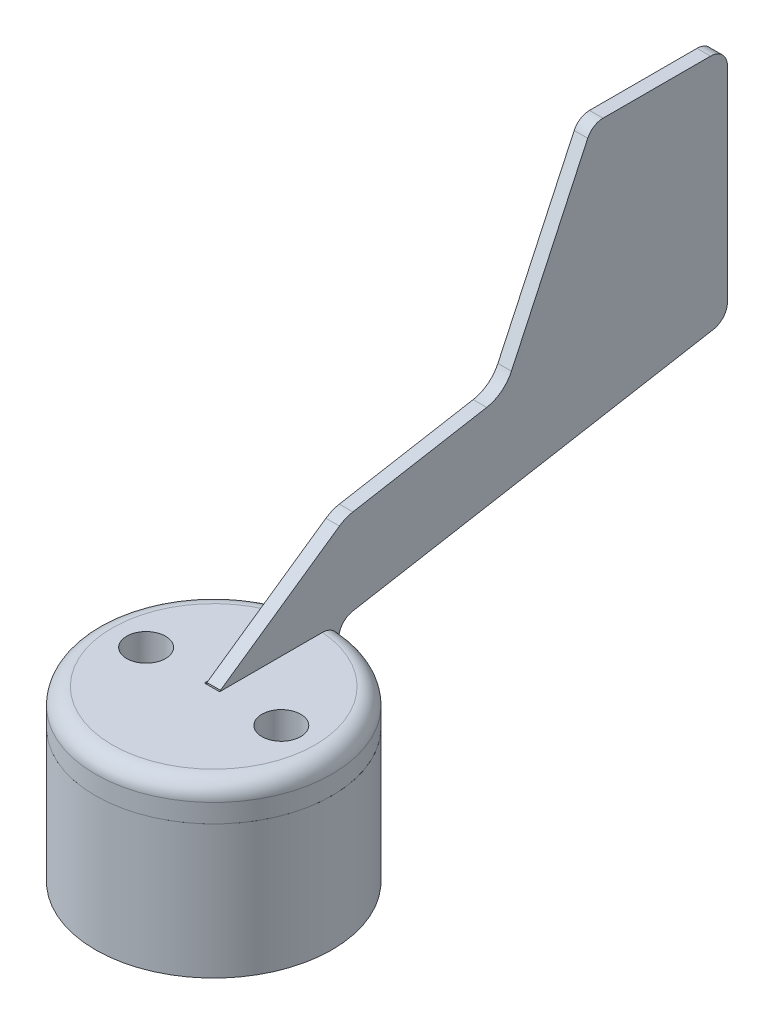
SolidWorks part; units mm, degrees
ref_plane "前视基准面" through (0, 0, 0) normal (0, 0, 1) x (1, 0, 0)
ref_plane "上视基准面" through (0, 0, 0) normal (0, 1, 0) x (1, 0, 0)
ref_plane "右视基准面" through (0, 0, 0) normal (1, 0, 0) x (0, 0, -1)
sketch "草图1" plane through (0, 0, 0) normal (1, 0, 0) x (0, 0, -1)
  line L1 (0, 0) -> (7, 0)
  line L2 (0, 0) -> (0, 10)
  line L3 (0, 10) -> (7, 10)
  line L4 (7, 0) -> (7, 10)
  dimension "D1" = 7
  dimension "D2" = 10
revolve "旋转1" add sketch "草图1" angle 360 about L2
sketch "草图2" plane through (0, 0, 0) normal (0, 1, 0) x (1, 0, 0)
  line L1 (-1.3847, -1.15) -> (1.3847, -1.15)
  arc A0 (1.3847, -1.15) -> (-1.3847, -1.15) centre (0, 0) ccw
  point P8 (0, -1.15)
  dimension "D1" = 3.6
extrude "切除-拉伸1" cut sketch "草图2" along normal blind 6.5
sketch "草图4" plane through (0, 0, 0) normal (1, 0, 0) x (0, 0, -1)
  line L1 (7, 10) -> (-7, 10) construction
  line L2 (16.7779, 16.8012) -> (22, 28)
  line L3 (22, 28) -> (30, 28)
  line L4 (30, 28) -> (30, 14.0555)
  line L5 (30, 14.0555) -> (7, 10)
  line L6 (16.7779, 16.8012) -> (7.4008, 15.1478)
  line L7 (16.7779, 16.8012) -> (7, 10) construction
  line L8 (7, 0) -> (7, 10) construction
  line L9 (0, 10) -> (7, 10) construction
  line L10 (7, 10) -> (7, 8)
  line L11 (7, 8) -> (0, 8)
  line L12 (0, 8) -> (0, 10)
  line L13 (7.4008, 15.1478) -> (0, 10)
  dimension "D1" = 5
  dimension "D2" = 18
  dimension "D3" = 30
  dimension "D4" = 25
  dimension "D5" = 8
  dimension "D6" = 10
  dimension "D7" = 2
extrude "凸台-拉伸2" add sketch "草图4" along normal mid plane 0.8 separate body
sketch "草图5" plane through (0, 0, 0) normal (1, 0, 0) x (0, 0, -1)
  line L0 (-0.1, 10.1) -> (-0.1, 7.9)
  line L1 (0, 10) -> (7, 10) construction
  line L2 (0, 10) -> (0, 8) construction
  line L3 (0, 8) -> (7, 8) construction
  line L4 (7, 10) -> (7, 8) construction
  line L5 (-0.1, 7.9) -> (7.1, 7.9)
  line L6 (7.1, 10.1) -> (7.1, 7.9)
  line L7 (-0.1, 10.1) -> (7.1, 10.1)
  dimension "D1" = 0.1
extrude "切除-拉伸2" cut sketch "草图5" against normal mid plane 0.9
fillet "圆角1" radius 1 1 edges at (0, 10, 7)
fillet "圆角2" radius 1 2 edges at (0, 28, -22) (0, 10, -7)
sketch "草图6" plane through (0, 0, 0) normal (0, -1, 0) x (1, 0, 0)
  circle A1 centre (0, 0) radius 2.8
  circle A2 centre (0, 0) radius 6
  circle A3 centre (0, 0) radius 6
  circle A4 centre (0, 0) radius 1.8 construction
  dimension "D2" = 1
  dimension "D1" = 1
extrude "切除-拉伸3" cut sketch "草图6" against normal blind 6
fillet "圆角4" radius 1 2 edges at (0, 6, -6) (0, 6, -2.8)
fillet "圆角3" radius 2 2 edges at (0, 15.1478, -7.4008) (0, 16.8012, -16.7779)
sketch "草图8" plane through (0, 10, 0) normal (0, 1, 0) x (1, 0, 0)
  line L0 (0, -1000) -> (0, 49000) construction
  line L2 (0, 0) -> (7, 0) construction
  arc A0 (-0.45, 6.9855) -> (0.45, 6.9855) centre (0, 0) ccw construction
  circle A1 centre (4, 0) radius 1
  circle A2 centre (-4, 0) radius 1
  dimension "D1" = 2
  dimension "D2" = 8
extrude "切除-拉伸4" cut sketch "草图8" against normal blind 6
sketch "草图12" plane through (0, 0, 0) normal (1, 0, 0) x (0, 0, -1)
  line L0 (-7, 7.9) -> (7, 7.9)
  line L1 (-7, 9) -> (-7, 0) construction
  line L2 (7, 0) -> (7, 7.9) construction
  line L3 (-0.1, 7.9) -> (6.9855, 7.9) construction
split "分割1" trim tools "草图12" bodies to split 113 resulting bodies 117 118
sketch "草图13" plane through (0, 10, 0) normal (0, 1, 0) x (1, 0, 0)
  circle A0 centre (-4, 0) radius 1.15
  circle A1 centre (4, 0) radius 1.15
  dimension "D1" = 2.3
extrude "切除-拉伸6" cut sketch "草图13" against normal blind 2.8
fillet "圆角7" radius 1 2 edges at (0, 14.0555, -30) (0, 28, -30)
sketch "草图14" plane through (0, 0, 0) normal (0, -1, 0) x (1, 0, 0)
  line L0 (0.4, -2.1399) -> (0.4, -6.369)
  line L1 (-0.4, 2.1399) -> (0.4, 2.1399)
  line L2 (-0.4, 2.1399) -> (-0.4, 6.369)
  line L3 (-0.4, 6.369) -> (0.4, 6.369)
  line L4 (0.4, 2.1399) -> (0.4, 6.369)
  line L5 (0, 6.369) -> (0, 2.1399) construction
  line L6 (-0.4, 4.2544) -> (0.4, 4.2544) construction
  line L7 (0.4, -2.1399) -> (-0.4, -2.1399)
  line L8 (-0.4, -2.1399) -> (-0.4, -6.369)
  line L9 (0.4, -6.369) -> (-0.4, -6.369)
  point P0 (0, 4.2544)
  point P13 (0, 0)
  dimension "D1" = 0.8
  dimension "D2" = 2
extrude "凸台-拉伸3" add sketch "草图14" against normal up to surface (6 mm away) contours L2 L1 L4 L3 | L0 L9 L8 L7 up to face at (0, 6, -2.6062)
